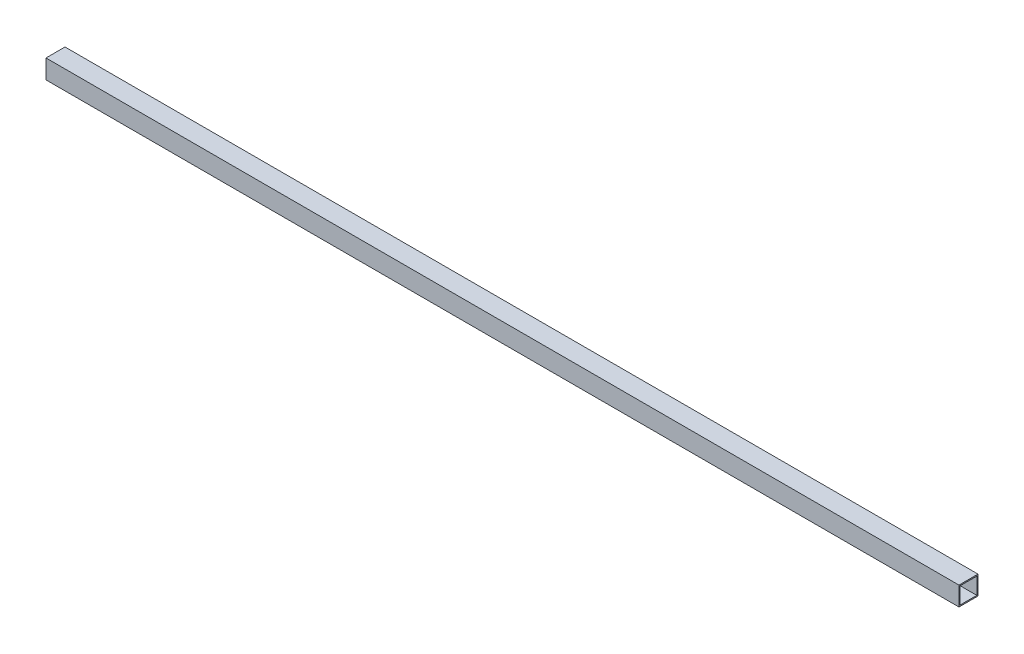
SolidWorks part; units mm, degrees
material "6061-T4 (SS)"
ref_plane "Front Plane" through (0, 0, 0) normal (0, 0, 1) x (1, 0, 0)
ref_plane "Top Plane" through (0, 0, 0) normal (0, 1, 0) x (1, 0, 0)
ref_plane "Right Plane" through (0, 0, 0) normal (1, 0, 0) x (0, 0, -1)
sketch "Sketch1" plane through (0, 0, 0) normal (1, 0, 0) x (0, 0, -1)
  line L0 (11.1125, -11.1125) -> (11.1125, 11.1125)
  line L1 (-12.7, -12.7) -> (12.7, -12.7)
  line L2 (-12.7, -12.7) -> (-12.7, 12.7)
  line L3 (-12.7, 12.7) -> (12.7, 12.7)
  line L4 (12.7, -12.7) -> (12.7, 12.7)
  line L5 (-12.7, -12.7) -> (12.7, 12.7) construction
  line L6 (-12.7, 12.7) -> (12.7, -12.7) construction
  line L7 (-11.1125, 11.1125) -> (11.1125, 11.1125)
  line L8 (-11.1125, -11.1125) -> (-11.1125, 11.1125)
  line L9 (-11.1125, -11.1125) -> (11.1125, -11.1125)
  point P0 (0, 0)
  dimension "D1" = 25.4
  dimension "D2" = 25.4
  dimension "D3" = 1.5875
extrude "Boss-Extrude1" add sketch "Sketch1" along normal blind 1219.2
